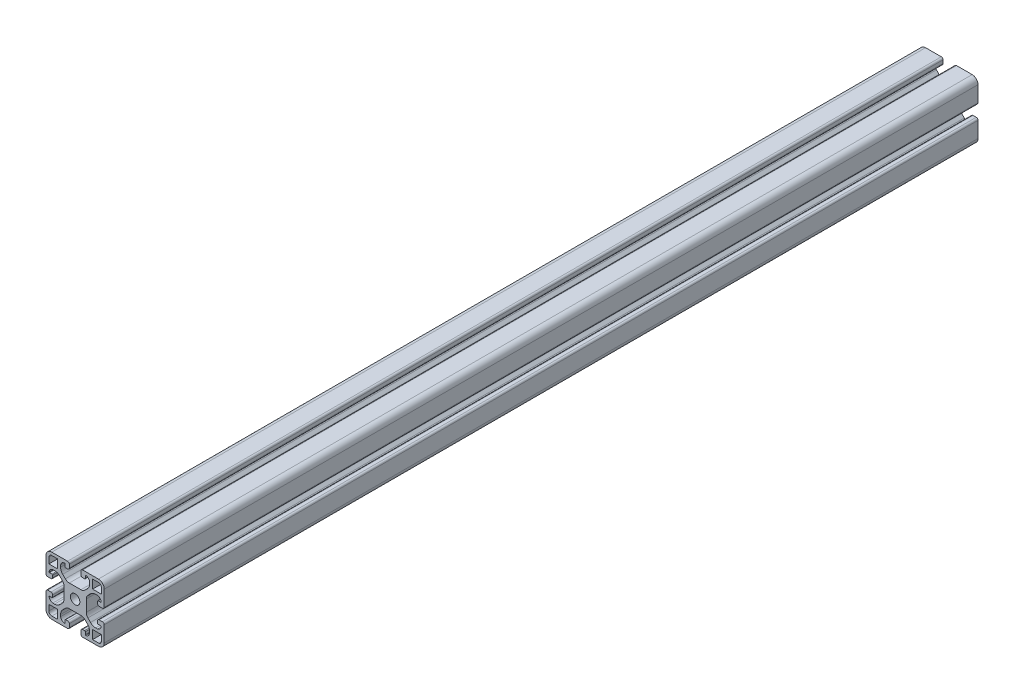
SolidWorks part; units mm, degrees
ref_plane "Alzado" through (0, 0, 0) normal (0, 0, 1) x (1, 0, 0)
ref_plane "Planta" through (0, 0, 0) normal (0, 1, 0) x (1, 0, 0)
ref_plane "Vista lateral" through (0, 0, 0) normal (1, 0, 0) x (0, 0, -1)
sketch "Croquis1" plane through (0, 0, 0) normal (0, 0, 1) x (1, 0, 0)
  line L0 (-12, -18) -> (-16, -18)
  line L1 (-18, -16) -> (-18, -12)
  line L2 (-18, -12) -> (-12, -12)
  line L3 (-12, -12) -> (-12, -18)
  line L4 (18, -16) -> (18, -12)
  line L5 (12, -18) -> (16, -18)
  line L6 (12, -12) -> (12, -18)
  line L7 (18, -12) -> (12, -12)
  line L8 (16, 18) -> (12, 18)
  line L9 (18, 12) -> (18, 16)
  line L10 (12, 12) -> (18, 12)
  line L11 (12, 18) -> (12, 12)
  line L12 (-18, 16) -> (-18, 12)
  line L13 (-12, 18) -> (-16, 18)
  line L14 (-12, 12) -> (-12, 18)
  line L15 (-18, 12) -> (-12, 12)
  line L16 (17.6386, 7) -> (15.9, 7)
  line L17 (15.4, 6.5) -> (15.4, 5.1441)
  line L18 (16.5441, 4) -> (18.8, 4)
  line L19 (20, 5.2) -> (20, 16)
  line L20 (16, 20) -> (5.2, 20)
  line L21 (4, 18.8) -> (4, 16.5441)
  line L22 (5.1441, 15.4) -> (6.5, 15.4)
  line L23 (7, 15.9) -> (7, 17.6386)
  line L24 (10, 15.3943) -> (10, 14.1334)
  line L25 (8.5264, 10.5757) -> (6.7325, 8.7818)
  line L26 (4, 7.65) -> (-4, 7.65)
  line L27 (-6.7325, 8.7818) -> (-8.5264, 10.5757)
  line L28 (-10, 14.1334) -> (-10, 15.3943)
  line L29 (-7, 17.6386) -> (-7, 15.9)
  line L30 (-6.5, 15.4) -> (-5.1441, 15.4)
  line L31 (-4, 16.5441) -> (-4, 18.8)
  line L32 (-5.2, 20) -> (-16, 20)
  line L33 (-20, 16) -> (-20, 5.2)
  line L34 (-18.8, 4) -> (-16.5441, 4)
  line L35 (-15.4, 5.1441) -> (-15.4, 6.5)
  line L36 (-15.9, 7) -> (-17.6386, 7)
  line L37 (-15.3943, 10) -> (-14.1334, 10)
  line L38 (-10.5757, 8.5264) -> (-8.7818, 6.7325)
  line L39 (-7.65, 4) -> (-7.65, -4)
  line L40 (-8.7818, -6.7325) -> (-10.5757, -8.5264)
  line L41 (-14.1334, -10) -> (-15.3943, -10)
  line L42 (-17.6386, -7) -> (-15.9, -7)
  line L43 (-15.4, -6.5) -> (-15.4, -5.1441)
  line L44 (-16.5441, -4) -> (-18.8, -4)
  line L45 (-20, -5.2) -> (-20, -16)
  line L46 (-16, -20) -> (-5.2, -20)
  line L47 (-4, -18.8) -> (-4, -16.5441)
  line L48 (-5.1441, -15.4) -> (-6.5, -15.4)
  line L49 (-7, -15.9) -> (-7, -17.6386)
  line L50 (-10, -15.3943) -> (-10, -14.1334)
  line L51 (-8.5264, -10.5757) -> (-6.7325, -8.7818)
  line L52 (-4, -7.65) -> (4, -7.65)
  line L53 (6.7325, -8.7818) -> (8.5264, -10.5757)
  line L54 (10, -14.1334) -> (10, -15.3943)
  line L55 (7, -17.6386) -> (7, -15.9)
  line L56 (6.5, -15.4) -> (5.1441, -15.4)
  line L57 (4, -16.5441) -> (4, -18.8)
  line L58 (5.2, -20) -> (16, -20)
  line L59 (20, -16) -> (20, -5.2)
  line L60 (18.8, -4) -> (16.5441, -4)
  line L61 (15.4, -5.1441) -> (15.4, -6.5)
  line L62 (15.9, -7) -> (17.6386, -7)
  line L63 (15.3943, -10) -> (14.1334, -10)
  line L64 (10.5757, -8.5264) -> (8.7818, -6.7325)
  line L65 (7.65, -4) -> (7.65, 4)
  line L66 (8.7818, 6.7325) -> (10.5757, 8.5264)
  line L67 (14.1334, 10) -> (15.3943, 10)
  circle A0 centre (0, 0) radius 3.25
  arc A1 (-18, -16) -> (-16, -18) centre (-16, -16) ccw
  arc A2 (16, -18) -> (18, -16) centre (16, -16) ccw
  arc A3 (18, 16) -> (16, 18) centre (16, 16) ccw
  arc A4 (-16, 18) -> (-18, 16) centre (-16, 16) ccw
  arc A5 (15.9, 7) -> (15.4, 6.5) centre (15.9, 6.5) ccw
  arc A6 (15.4, 5.1441) -> (16.5441, 4) centre (16.5441, 5.1441) ccw
  arc A7 (18.8, 4) -> (20, 5.2) centre (18.8, 5.2) ccw
  arc A8 (20, 16) -> (16, 20) centre (16, 16) ccw
  arc A9 (5.2, 20) -> (4, 18.8) centre (5.2, 18.8) ccw
  arc A10 (4, 16.5441) -> (5.1441, 15.4) centre (5.1441, 16.5441) ccw
  arc A11 (6.5, 15.4) -> (7, 15.9) centre (6.5, 15.9) ccw
  arc A12 (7.2726, 17.8878) -> (7, 17.6386) centre (7.2502, 17.6386) ccw
  arc A13 (10, 15.3943) -> (7.2726, 17.8878) centre (7.0001, 14.8514) ccw
  arc A14 (8.5264, 10.5757) -> (10, 14.1334) centre (4.9687, 14.1334) ccw
  arc A15 (4, 7.65) -> (6.7325, 8.7818) centre (4, 11.5144) ccw
  arc A16 (-6.7325, 8.7818) -> (-4, 7.65) centre (-4, 11.5144) ccw
  arc A17 (-10, 14.1334) -> (-8.5264, 10.5757) centre (-4.9687, 14.1334) ccw
  arc A18 (-7.2726, 17.8878) -> (-10, 15.3943) centre (-7.0001, 14.8514) ccw
  arc A19 (-7, 17.6386) -> (-7.2726, 17.8878) centre (-7.2502, 17.6386) ccw
  arc A20 (-7, 15.9) -> (-6.5, 15.4) centre (-6.5, 15.9) ccw
  arc A21 (-5.1441, 15.4) -> (-4, 16.5441) centre (-5.1441, 16.5441) ccw
  arc A22 (-4, 18.8) -> (-5.2, 20) centre (-5.2, 18.8) ccw
  arc A23 (-16, 20) -> (-20, 16) centre (-16, 16) ccw
  arc A24 (-20, 5.2) -> (-18.8, 4) centre (-18.8, 5.2) ccw
  arc A25 (-16.5441, 4) -> (-15.4, 5.1441) centre (-16.5441, 5.1441) ccw
  arc A26 (-15.4, 6.5) -> (-15.9, 7) centre (-15.9, 6.5) ccw
  arc A27 (-17.8878, 7.2726) -> (-17.6386, 7) centre (-17.6386, 7.2502) ccw
  arc A28 (-15.3943, 10) -> (-17.8878, 7.2726) centre (-14.8514, 7.0001) ccw
  arc A29 (-10.5757, 8.5264) -> (-14.1334, 10) centre (-14.1334, 4.9687) ccw
  arc A30 (-7.65, 4) -> (-8.7818, 6.7325) centre (-11.5144, 4) ccw
  arc A31 (-8.7818, -6.7325) -> (-7.65, -4) centre (-11.5144, -4) ccw
  arc A32 (-14.1334, -10) -> (-10.5757, -8.5264) centre (-14.1334, -4.9687) ccw
  arc A33 (-17.8878, -7.2726) -> (-15.3943, -10) centre (-14.8514, -7.0001) ccw
  arc A34 (-17.6386, -7) -> (-17.8878, -7.2726) centre (-17.6386, -7.2502) ccw
  arc A35 (-15.9, -7) -> (-15.4, -6.5) centre (-15.9, -6.5) ccw
  arc A36 (-15.4, -5.1441) -> (-16.5441, -4) centre (-16.5441, -5.1441) ccw
  arc A37 (-18.8, -4) -> (-20, -5.2) centre (-18.8, -5.2) ccw
  arc A38 (-20, -16) -> (-16, -20) centre (-16, -16) ccw
  arc A39 (-5.2, -20) -> (-4, -18.8) centre (-5.2, -18.8) ccw
  arc A40 (-4, -16.5441) -> (-5.1441, -15.4) centre (-5.1441, -16.5441) ccw
  arc A41 (-6.5, -15.4) -> (-7, -15.9) centre (-6.5, -15.9) ccw
  arc A42 (-7.2726, -17.8878) -> (-7, -17.6386) centre (-7.2502, -17.6386) ccw
  arc A43 (-10, -15.3943) -> (-7.2726, -17.8878) centre (-7.0001, -14.8514) ccw
  arc A44 (-8.5264, -10.5757) -> (-10, -14.1334) centre (-4.9687, -14.1334) ccw
  arc A45 (-4, -7.65) -> (-6.7325, -8.7818) centre (-4, -11.5144) ccw
  arc A46 (6.7325, -8.7818) -> (4, -7.65) centre (4, -11.5144) ccw
  arc A47 (10, -14.1334) -> (8.5264, -10.5757) centre (4.9687, -14.1334) ccw
  arc A48 (7.2726, -17.8878) -> (10, -15.3943) centre (7.0001, -14.8514) ccw
  arc A49 (7, -17.6386) -> (7.2726, -17.8878) centre (7.2502, -17.6386) ccw
  arc A50 (7, -15.9) -> (6.5, -15.4) centre (6.5, -15.9) ccw
  arc A51 (5.1441, -15.4) -> (4, -16.5441) centre (5.1441, -16.5441) ccw
  arc A52 (4, -18.8) -> (5.2, -20) centre (5.2, -18.8) ccw
  arc A53 (16, -20) -> (20, -16) centre (16, -16) ccw
  arc A54 (20, -5.2) -> (18.8, -4) centre (18.8, -5.2) ccw
  arc A55 (16.5441, -4) -> (15.4, -5.1441) centre (16.5441, -5.1441) ccw
  arc A56 (15.4, -6.5) -> (15.9, -7) centre (15.9, -6.5) ccw
  arc A57 (17.8878, -7.2726) -> (17.6386, -7) centre (17.6386, -7.2502) ccw
  arc A58 (15.3943, -10) -> (17.8878, -7.2726) centre (14.8514, -7.0001) ccw
  arc A59 (10.5757, -8.5264) -> (14.1334, -10) centre (14.1334, -4.9687) ccw
  arc A60 (7.65, -4) -> (8.7818, -6.7325) centre (11.5144, -4) ccw
  arc A61 (8.7818, 6.7325) -> (7.65, 4) centre (11.5144, 4) ccw
  arc A62 (14.1334, 10) -> (10.5757, 8.5264) centre (14.1334, 4.9687) ccw
  arc A63 (17.8878, 7.2726) -> (15.3943, 10) centre (14.8514, 7.0001) ccw
  arc A64 (17.6386, 7) -> (17.8878, 7.2726) centre (17.6386, 7.2502) ccw
extrude "Saliente-Extruir1" add sketch "Croquis1" along normal blind 600
